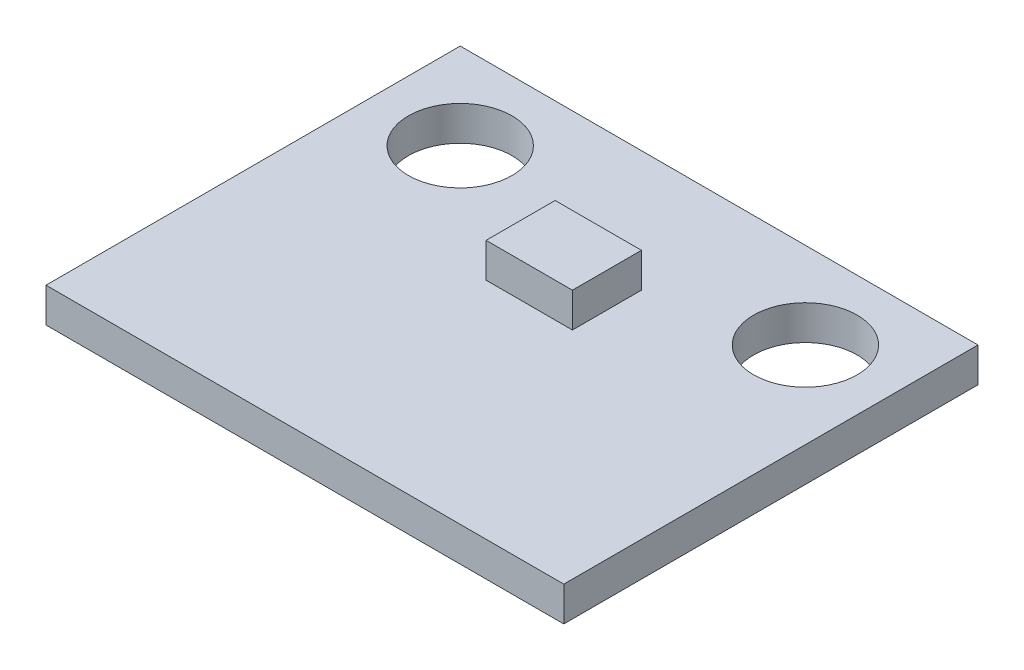
SolidWorks part; units mm, degrees
ref_plane "Front Plane" through (0, 0, 0) normal (0, 0, 1) x (1, 0, 0)
ref_plane "Top Plane" through (0, 0, 0) normal (0, 1, 0) x (1, 0, 0)
ref_plane "Right Plane" through (0, 0, 0) normal (1, 0, 0) x (0, 0, -1)
sketch "Sketch1" plane through (0, 0, 0) normal (0, 1, 0) x (1, 0, 0)
  line L1 (-7.5, 6) -> (7.5, 6)
  line L2 (-7.5, 6) -> (-7.5, -6)
  line L3 (-7.5, -6) -> (7.5, -6)
  line L4 (7.5, 6) -> (7.5, -6)
  line L5 (-7.5, 6) -> (7.5, -6) construction
  line L6 (-7.5, -6) -> (7.5, 6) construction
  circle A0 centre (-5, 3.5) radius 1.5
  circle A1 centre (5, 3.5) radius 1.5
  point P0 (0, 0)
  point P10 (0, 0)
  dimension "D3" = 3
  dimension "D1" = 15
  dimension "D2" = 12
  dimension "D4" = 2.5
  dimension "D5" = 2.5
  dimension "D6" = 2.5
extrude "PCB" add sketch "Sketch1" along normal blind 1
sketch "Sketch2" plane through (0, 1, 0) normal (0, 1, 0) x (1, 0, 0)
  line L1 (-1.25, 2.5) -> (1.25, 2.5)
  line L2 (-1.25, 2.5) -> (-1.25, 0.5)
  line L3 (-1.25, 0.5) -> (1.25, 0.5)
  line L4 (1.25, 2.5) -> (1.25, 0.5)
  line L5 (-1.25, 2.5) -> (1.25, 0.5) construction
  line L6 (-1.25, 0.5) -> (1.25, 2.5) construction
  circle A0 centre (5, 3.5) radius 1.5 construction
  point P0 (0, 1.5)
  point P5 (0, 0)
  dimension "D1" = 2
  dimension "D2" = 2.5
  dimension "D3" = 2
extrude "Sensor" add sketch "Sketch2" along normal blind 1
